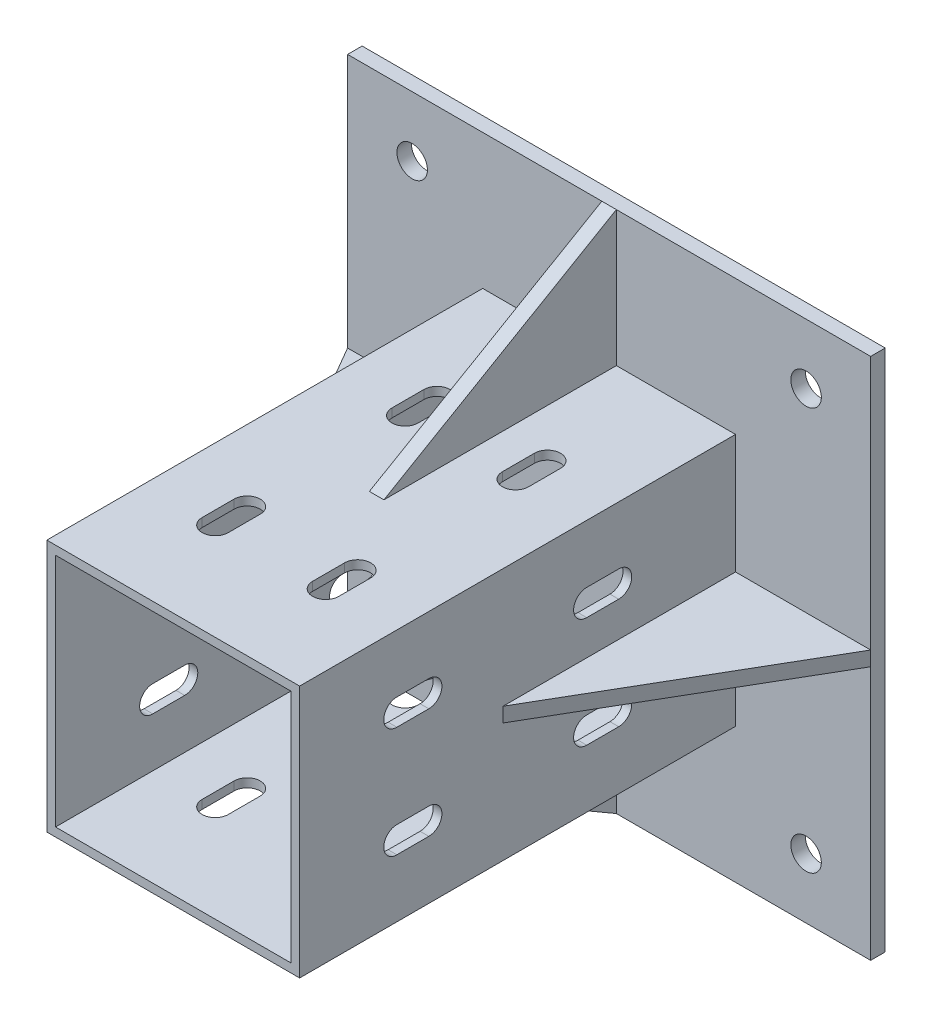
SolidWorks part; units mm, degrees
ref_plane "前视基准面" through (0, 0, 0) normal (0, 0, 1) x (1, 0, 0)
ref_plane "上视基准面" through (0, 0, 0) normal (0, 1, 0) x (1, 0, 0)
ref_plane "右视基准面" through (0, 0, 0) normal (1, 0, 0) x (0, 0, -1)
sketch "草图1" plane through (0, 0, 0) normal (0, 0, 1) x (1, 0, 0)
  line L1 (-90, 90) -> (90, 90)
  line L2 (-90, 90) -> (-90, -90)
  line L3 (-90, -90) -> (90, -90)
  line L4 (90, 90) -> (90, -90)
  line L5 (-90, 90) -> (90, -90) construction
  line L6 (-90, -90) -> (90, 90) construction
  point P0 (0, 0)
  dimension "D1" = 180
  dimension "D2" = 180
extrude "凸台-拉伸1" add sketch "草图1" along normal blind 5
sketch "草图2" plane through (0, 0, 5) normal (0, 0, 1) x (1, 0, 0)
  circle A0 centre (-67.7768, 69.2999) radius 5.25
  dimension "D1" = 10.5
extrude "切除-拉伸1" cut sketch "草图2" against normal through all
mirror "镜向1" about plane through (0, 0, 0) normal (0, 1, 0) of "切除-拉伸1"
mirror "镜向2" about plane through (0, 0, 0) normal (1, 0, 0) of "镜向1", "切除-拉伸1"
sketch "草图3" plane through (0, 0, 5) normal (0, 0, 1) x (1, 0, 0)
  line L1 (-43.5, 43.5) -> (43.5, 43.5)
  line L2 (-43.5, 43.5) -> (-43.5, -43.5)
  line L3 (-43.5, -43.5) -> (43.5, -43.5)
  line L4 (43.5, 43.5) -> (43.5, -43.5)
  line L5 (-43.5, 43.5) -> (43.5, -43.5) construction
  line L6 (-43.5, -43.5) -> (43.5, 43.5) construction
  line L7 (-40.5, 40.5) -> (40.5, 40.5)
  line L8 (-40.5, 40.5) -> (-40.5, -40.5)
  line L9 (-40.5, -40.5) -> (40.5, -40.5)
  line L10 (40.5, 40.5) -> (40.5, -40.5)
  line L11 (-40.5, 40.5) -> (40.5, -40.5) construction
  line L12 (-40.5, -40.5) -> (40.5, 40.5) construction
  point P0 (0, 0)
  point P6 (0, 0)
  dimension "D1" = 87
  dimension "D2" = 87
  dimension "D3" = 81
  dimension "D4" = 81
extrude "凸台-拉伸2" add sketch "草图3" along normal blind 150
sketch "草图4" plane through (0, 0, 0) normal (0, 1, 0) x (1, 0, 0)
  line L0 (43.5, -5) -> (90, -5)
  line L2 (90, -5) -> (43.5, -85)
  line L3 (43.5, -155) -> (43.5, -5) construction
  line L4 (43.5, -85) -> (43.5, -5)
  dimension "D1" = 80
extrude "凸台-拉伸3" add sketch "草图4" along normal blind 2.5 and the other way blind 2.5
mirror "镜向3" about plane through (0, 0, 0) normal (1, 0, 0) of "凸台-拉伸3"
sketch "草图5" plane through (0, 0, 0) normal (1, 0, 0) x (0, 0, -1)
  line L0 (-5, 43.5) -> (-5, 90)
  line L1 (-5, 90) -> (-85, 43.5)
  line L2 (-85, 43.5) -> (-5, 43.5)
  dimension "D1" = 80
extrude "凸台-拉伸4" add sketch "草图5" along normal blind 2.5 and the other way blind 2.5
mirror "镜向4" about plane through (0, 0, 0) normal (0, 1, 0) of "凸台-拉伸4"
sketch "草图6" plane through (0, -43.5, 0) normal (0, -1, 0) x (1, 0, 0)
  line L0 (-19.0069, 121.5478) -> (-19.0069, 110.5478) construction
  line L1 (-14.5069, 121.5478) -> (-14.5069, 110.5478)
  line L2 (-23.5069, 121.5478) -> (-23.5069, 110.5478)
  line L3 (-19.0069, 56.2145) -> (-19.0069, 45.2145) construction
  line L4 (-14.5069, 56.2145) -> (-14.5069, 45.2145)
  line L5 (-23.5069, 56.2145) -> (-23.5069, 45.2145)
  arc A0 (-14.5069, 121.5478) -> (-23.5069, 121.5478) centre (-19.0069, 121.5478) ccw
  arc A1 (-23.5069, 110.5478) -> (-14.5069, 110.5478) centre (-19.0069, 110.5478) ccw
  arc A2 (-14.5069, 56.2145) -> (-23.5069, 56.2145) centre (-19.0069, 56.2145) ccw
  arc A3 (-23.5069, 45.2145) -> (-14.5069, 45.2145) centre (-19.0069, 45.2145) ccw
  point P2 (-19.0069, 116.0478)
  point P9 (-19.0069, 50.7145)
  dimension "D2" = 4.5
  dimension "D1" = 11
extrude "切除-拉伸2" cut sketch "草图6" against normal through all
mirror "镜向5" about plane through (0, 0, 0) normal (1, 0, 0) of "切除-拉伸2"
ref_plane "基准面1" through (0, 0, 0) normal (0.7071, -0.7071, 0) x (0, 0, -1)
mirror "镜向6" about plane through (0, 0, 0) normal (0.7071, -0.7071, 0) of "镜向5", "切除-拉伸2"
